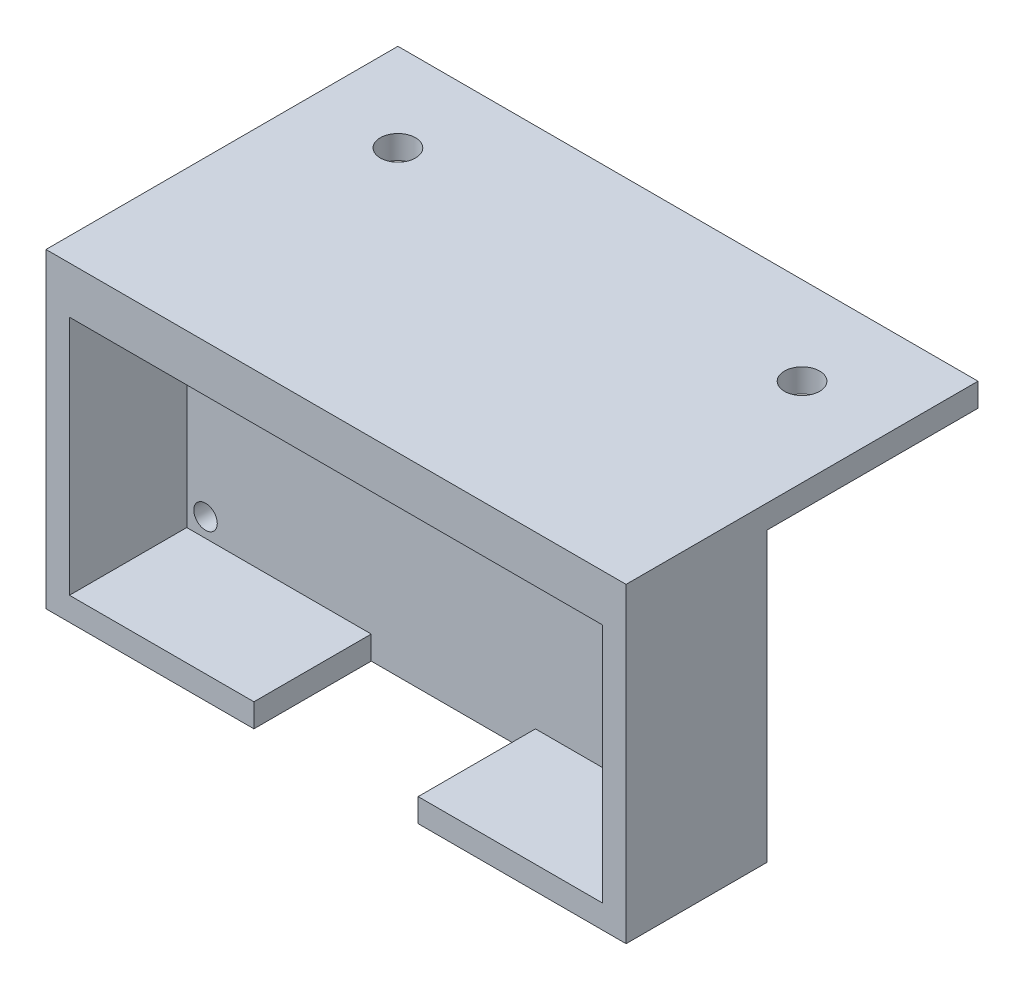
SolidWorks part; units mm, degrees
ref_plane "Plan de face" through (0, 0, 0) normal (0, 0, 1) x (1, 0, 0)
ref_plane "Plan de dessus" through (0, 0, 0) normal (0, 1, 0) x (1, 0, 0)
ref_plane "Plan de droite" through (0, 0, 0) normal (1, 0, 0) x (0, 0, -1)
sketch "Esquisse1" plane through (0, 0, 0) normal (0, 0, 1) x (1, 0, 0)
  line L0 (8.7408, -15.0018) -> (26.4658, -15.0018)
  line L1 (-22.9842, 9.5282) -> (26.4658, 9.5282)
  line L2 (-22.9842, 9.5282) -> (-22.9842, -15.0018)
  line L3 (-22.9842, -15.0018) -> (-5.2592, -15.0018)
  line L4 (26.4658, 9.5282) -> (26.4658, -15.0018)
  line L5 (-20.9842, 7.5282) -> (24.4658, 7.5282)
  line L6 (-20.9842, 7.5282) -> (-20.9842, -13.0018)
  line L7 (-20.9842, -13.0018) -> (-5.2592, -13.0018)
  line L8 (24.4658, 7.5282) -> (24.4658, -13.0018)
  line L9 (8.7408, -13.0018) -> (24.4658, -13.0018)
  line L10 (-5.2592, -13.0018) -> (-5.2592, -15.0018)
  line L12 (8.7408, -13.0018) -> (8.7408, -15.0018)
  dimension "D1" = 49.45
  dimension "D2" = 45.45
  dimension "D3" = 2
  dimension "D4" = 2
  dimension "D5" = 14
  dimension "D6" = 17.725
  dimension "D8" = 24.53
extrude "Boss.-Extru.1" add sketch "Esquisse1" along normal blind 10
sketch "Esquisse2" plane through (0, 0, 0) normal (0, 0, -1) x (-1, 0, 0)
  line L1 (22.9842, 9.5282) -> (-26.4658, 9.5282)
  line L2 (22.9842, 9.5282) -> (22.9842, -15.0018)
  line L3 (22.9842, -15.0018) -> (-26.4658, -15.0018)
  line L4 (-26.4658, 9.5282) -> (-26.4658, -15.0018)
extrude "Boss.-Extru.2" add sketch "Esquisse2" along normal blind 2
sketch "Esquisse3" plane through (0, 0, 0) normal (0, 0, 1) x (1, 0, 0)
  line L0 (-20.9842, -13.0018) -> (-20.9842, 7.5282) construction
  line L1 (-5.2592, -13.0018) -> (-20.9842, -13.0018) construction
  line L2 (-20.9842, -2.7368) -> (24.4658, -2.7368) construction
  line L3 (24.4658, 7.5282) -> (24.4658, -13.0018) construction
  line L4 (1.7408, -2.7368) -> (1.7408, 7.5282) construction
  line L5 (-20.9842, 7.5282) -> (24.4658, 7.5282) construction
  line L6 (1.7408, 7.5282) -> (1.7408, -15.0018) construction
  line L7 (8.7408, -15.0018) -> (-5.2592, -15.0018) construction
  circle A0 centre (-19.3842, -11.4018) radius 1
  circle A1 centre (22.8658, -11.4018) radius 1
  circle A2 centre (22.8658, 5.9282) radius 1
  circle A3 centre (-19.3842, 5.9282) radius 1
  dimension "D1" = 2
  dimension "D2" = 1.6
  dimension "D3" = 1.6
extrude "Enlèv. mat.-Extru.1" cut sketch "Esquisse3" against normal blind 2
sketch "Esquisse7" plane through (0, 9.5282, 0) normal (0, 1, 0) x (1, 0, 0)
  line L1 (-22.9842, -10) -> (26.4658, -10)
  line L2 (-22.9842, -10) -> (-22.9842, 20)
  line L3 (-22.9842, 20) -> (26.4658, 20)
  line L4 (26.4658, -10) -> (26.4658, 20)
  dimension "D1" = 30
extrude "Boss.-Extru.3" add sketch "Esquisse7" along normal blind 2
sketch "Esquisse8" plane through (0, 11.5282, 0) normal (0, 1, 0) x (1, 0, 0)
  line L0 (1.7408, 20) -> (1.7408, -10) construction
  line L1 (26.4658, 20) -> (-22.9842, 20) construction
  line L2 (-22.9842, -10) -> (26.4658, -10) construction
  line L3 (-22.9842, 20) -> (-22.9842, -10) construction
  circle A0 centre (-15.4842, 12.5) radius 1.5
  circle A1 centre (18.9658, 12.5) radius 1.5
  dimension "D1" = 7.5
  dimension "D2" = 7.5
extrude "Enlèv. mat.-Extru.2" cut sketch "Esquisse8" against normal blind 2
